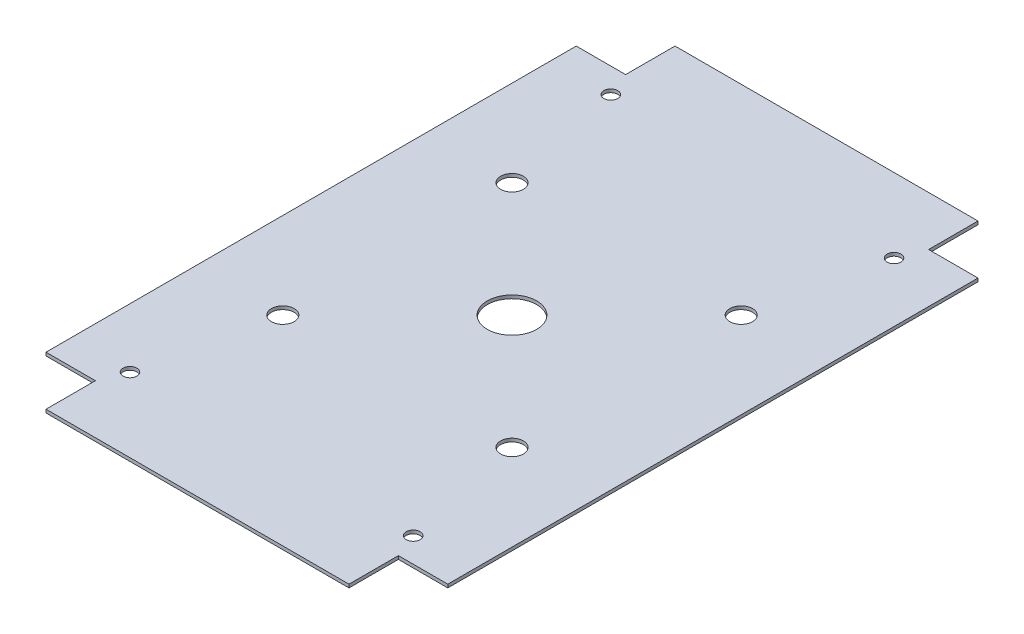
SolidWorks part; units mm, degrees
ref_plane "Front Plane" through (0, 0, 0) normal (0, 0, 1) x (1, 0, 0)
ref_plane "Top Plane" through (0, 0, 0) normal (0, 1, 0) x (1, 0, 0)
ref_plane "Right Plane" through (0, 0, 0) normal (1, 0, 0) x (0, 0, -1)
sketch "Sketch1" plane through (0, 0, 0) normal (0, 1, 0) x (1, 0, 0)
  line L0 (-46, -80.5) -> (-61, -80.5)
  line L1 (-34.8, 34.8) -> (34.8, 34.8) construction
  line L2 (-34.8, 34.8) -> (-34.8, -34.8) construction
  line L3 (-34.8, -34.8) -> (34.8, -34.8) construction
  line L4 (34.8, 34.8) -> (34.8, -34.8) construction
  line L5 (-34.8, 34.8) -> (34.8, -34.8) construction
  line L6 (-34.8, -34.8) -> (34.8, 34.8) construction
  line L7 (-43, 43) -> (43, 43) construction
  line L8 (-43, 43) -> (-43, -43) construction
  line L9 (-43, -43) -> (43, -43) construction
  line L10 (43, 43) -> (43, -43) construction
  line L11 (-43, 43) -> (43, -43) construction
  line L12 (-43, -43) -> (43, 43) construction
  line L13 (-46, 80.5) -> (46, 80.5) construction
  line L14 (-46, 80.5) -> (-46, -80.5) construction
  line L15 (-46, -80.5) -> (46, -80.5) construction
  line L16 (-62.5, 0) -> (0, 0) construction
  line L17 (46, 80.5) -> (46, -80.5) construction
  line L18 (-46, 80.5) -> (46, -80.5) construction
  line L19 (-46, -80.5) -> (46, 80.5) construction
  line L21 (-61, -80.5) -> (-61, 80.5)
  line L25 (-61, 80.5) -> (-46, 80.5)
  line L26 (-46, 80.5) -> (-46, 95.5)
  line L27 (-43, 73) -> (43, 73) construction
  line L28 (-43, 73) -> (-43, -73) construction
  line L29 (-43, -73) -> (43, -73) construction
  line L30 (43, 73) -> (43, -73) construction
  line L31 (-43, 73) -> (43, -73) construction
  line L32 (-43, -73) -> (43, 73) construction
  line L33 (-46, 95.5) -> (46, 95.5)
  line L34 (46, 95.5) -> (46, 80.5)
  line L35 (46, 80.5) -> (61, 80.5)
  line L36 (61, 80.5) -> (61, -80.5)
  line L37 (61, -80.5) -> (46, -80.5)
  line L38 (46, -80.5) -> (46, -95.5)
  line L39 (46, -95.5) -> (-46, -95.5)
  line L40 (-46, -95.5) -> (-46, -80.5)
  circle A0 centre (0, 0) radius 36.5 construction
  circle A1 centre (-34.8, 34.8) radius 3.45
  circle A2 centre (34.8, 34.8) radius 3.45
  circle A3 centre (34.8, -34.8) radius 3.45
  circle A4 centre (-34.8, -34.8) radius 3.45
  circle A5 centre (0, 0) radius 7.5
  circle A26 centre (-43, -73) radius 2.1
  circle A27 centre (43, -73) radius 2.1
  circle A30 centre (-43, 73) radius 2.1
  circle A31 centre (43, 73) radius 2.1
  point P0 (0, 0)
  dimension "D1" = 69.6
  dimension "D2" = 86
  dimension "D3" = 146
  dimension "D4" = 6.9
  dimension "D8" = 7.5
  dimension "D9" = 15
  dimension "D6" = 4.2
  dimension "D5" = 86
  dimension "D7" = 3
  dimension "D10" = 92
extrude "Boss-Extrude1" add sketch "Sketch1" along normal blind 1
